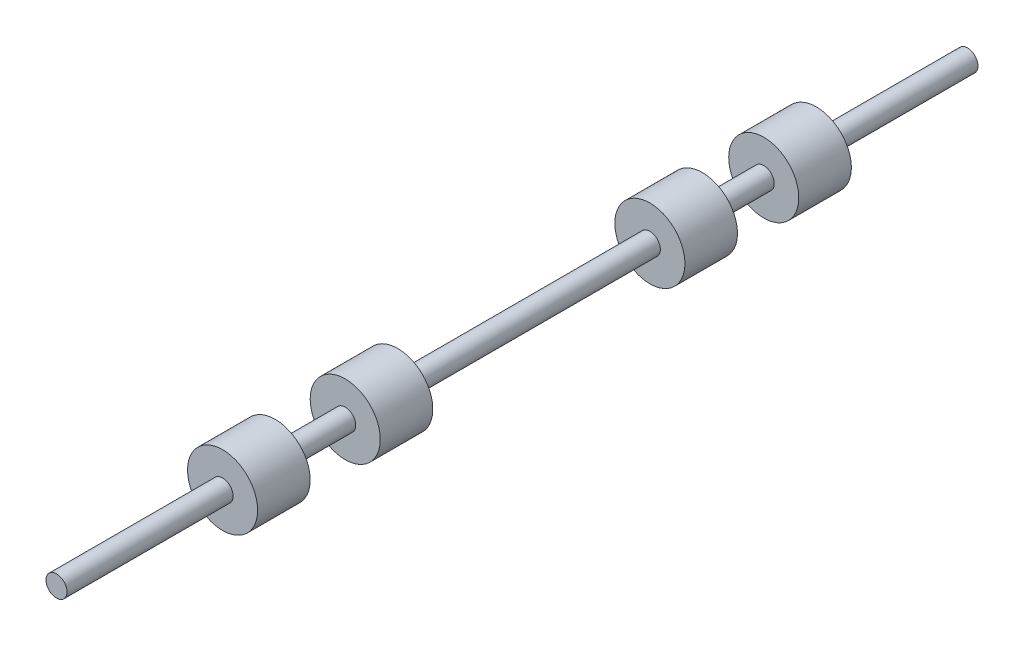
SolidWorks part; units mm, degrees
ref_plane "Front Plane" through (0, 0, 0) normal (0, 0, 1) x (1, 0, 0)
ref_plane "Top Plane" through (0, 0, 0) normal (0, 1, 0) x (1, 0, 0)
ref_plane "Right Plane" through (0, 0, 0) normal (1, 0, 0) x (0, 0, -1)
sketch "Sketch1" plane through (0, 0, 0) normal (0, 0, 1) x (1, 0, 0)
  circle A0 centre (0, 0) radius 0.3
  dimension "D1" = 0.6
extrude "Boss-Extrude1" add sketch "Sketch1" along normal blind 26
sketch "Sketch2" plane through (0, 0, 0) normal (0, 1, 0) x (1, 0, 0)
  line L0 (0, 0) -> (0, -26) construction
  line L1 (-0.3, -26) -> (0.3, -26) construction
  line L2 (0, -6.69) -> (2.7912, -6.69) construction
  line L3 (0, -4.315) -> (1, -4.315)
  line L4 (0, -4.315) -> (0, -5.815)
  line L5 (0, -5.815) -> (1, -5.815)
  line L6 (1, -4.315) -> (1, -5.815)
  line L7 (0, -7.565) -> (1, -7.565)
  line L8 (0, -7.565) -> (0, -9.065)
  line L9 (0, -9.065) -> (1, -9.065)
  line L10 (1, -7.565) -> (1, -9.065)
  line L11 (0, -18.76) -> (2.5878, -18.76) construction
  line L12 (0, -16.26) -> (1, -16.26)
  line L13 (0, -16.26) -> (0, -17.76)
  line L14 (0, -17.76) -> (1, -17.76)
  line L15 (1, -16.26) -> (1, -17.76)
  line L16 (0, -19.76) -> (1, -19.76)
  line L17 (0, -19.76) -> (0, -21.26)
  line L18 (0, -21.26) -> (1, -21.26)
  line L19 (1, -19.76) -> (1, -21.26)
  dimension "D1" = 1
  dimension "D2" = 1.5
  dimension "D3" = 1.75
  dimension "D4" = 2
  dimension "D5" = 1.5
  dimension "D6" = 1
  dimension "D7" = 7.24
  dimension "D8" = 12.07
revolve "Revolve1" add sketch "Sketch2" angle 360 about L0
